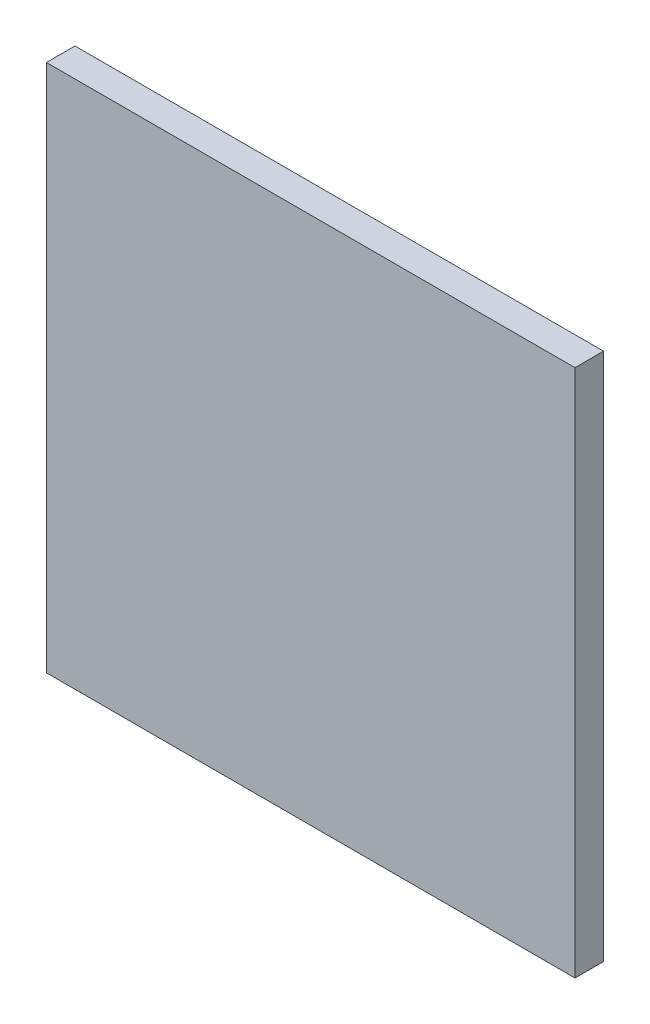
SolidWorks part; units mm, degrees
ref_plane "Alzado" through (0, 0, 0) normal (0, 0, 1) x (1, 0, 0)
ref_plane "Planta" through (0, 0, 0) normal (0, 1, 0) x (1, 0, 0)
ref_plane "Vista lateral" through (0, 0, 0) normal (1, 0, 0) x (0, 0, -1)
sketch "Croquis1" plane through (0, 0, 0) normal (0, 0, 1) x (1, 0, 0)
  line L0 (227.2469, 511.3055) -> (1136.2343, 511.3055) construction
  line L1 (605.1234, 694.282) -> (975.1234, 694.282)
  line L2 (975.1234, 694.282) -> (975.1234, 324.282)
  line L3 (975.1234, 324.282) -> (605.1234, 324.282)
  line L4 (605.1234, 324.282) -> (605.1234, 694.282)
  line L5 (0, 0) -> (605.1234, 0) construction
  line L6 (605.1234, 0) -> (605.1234, 324.282) construction
  dimension "D1" = 370
  dimension "D2" = 370
extrude "Saliente-Extruir1" add sketch "Croquis1" along normal blind 20 contours L2 L3 L4 L1
